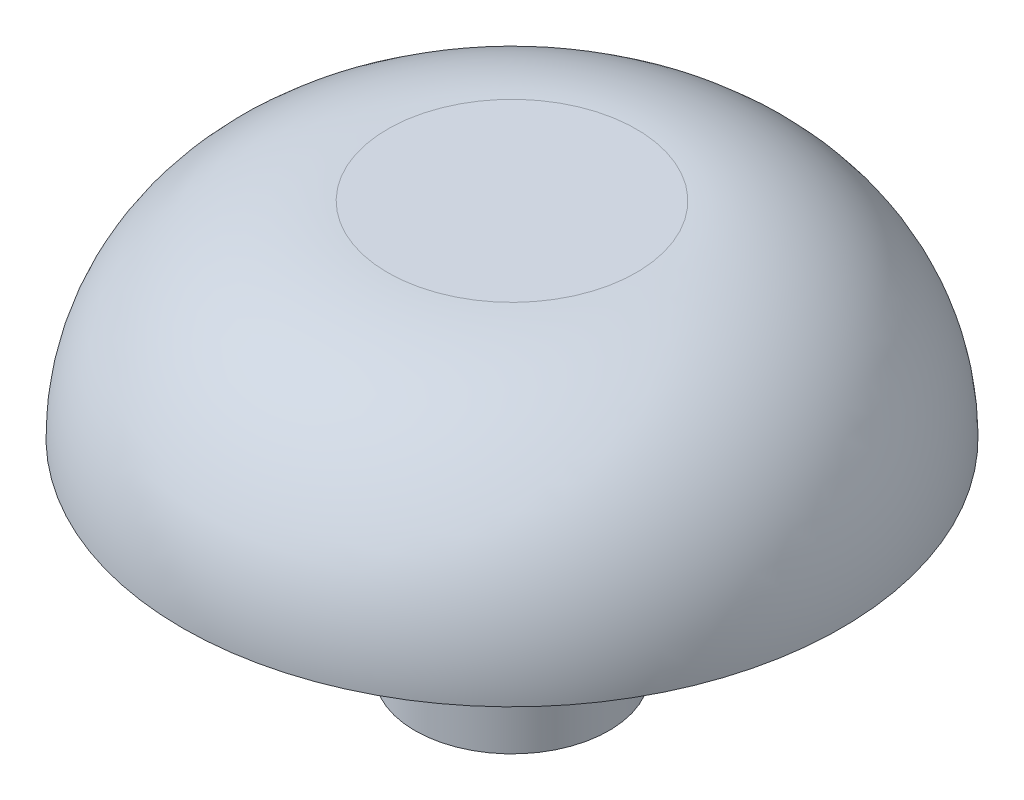
SolidWorks part; units mm, degrees
material "PE Alta Densidade"
ref_plane "Plano frontal" through (0, 0, 0) normal (0, 0, 1) x (1, 0, 0)
ref_plane "Plano superior" through (0, 0, 0) normal (0, 1, 0) x (1, 0, 0)
ref_plane "Plano direito" through (0, 0, 0) normal (1, 0, 0) x (0, 0, -1)
sketch "Esboço1" plane through (0, 0, 0) normal (0, 0, 1) x (1, 0, 0)
  line L0 (0, 0) -> (0, -16.5)
  line L1 (0, 0) -> (5, 0)
  line L2 (2, -2) -> (5, -2) construction
  line L5 (11.25, -8.25) -> (13.25, -8.25)
  line L6 (3.9, -2) -> (5, -2)
  line L8 (0, -16.5) -> (3.9, -16.5)
  line L9 (3.9, -16.5) -> (3.9, -2)
  line L11 (2.0938, -14.5) -> (2.0938, -2) construction
  line L12 (2, -2) -> (2, -14.5) construction
  line L13 (2, -14.5) -> (2.0938, -14.5) construction
  line L14 (0, -16.5) -> (4.0938, -16.5) construction
  line L15 (4.0938, -16.5) -> (4.0938, -2) construction
  arc A0 (5, 0) -> (13.25, -8.25) centre (5, -8.25) cw
  arc A1 (5, -2) -> (11.25, -8.25) centre (5, -8.25) cw
  dimension "D1" = 16.5
  dimension "D5" = 2
  dimension "D2" = 13.25
  dimension "D3" = 5
  dimension "D4" = 3.9
revolve "Revolução1" add sketch "Esboço1" angle 360 about L0
hole_wizard "Furo roscado de M41" positions "Esboço2" profile "Esboço3" tap size "M4" standard "DIN"
sketch "Esboço2" plane through (0, -16.5, 0) normal (0, -1, 0) x (-1, 0, 0)
  point P0 (0, 0)
sketch "Esboço3" plane through (0, -16.5, 0) normal (1, 0, 0) x (0, 0, -1)
  line L0 (0, 0) -> (0, 12.4914)
  line L1 (0, 12.4914) -> (1.65, 11.5)
  line L2 (1.65, 11.5) -> (1.65, 0.375)
  line L3 (1.65, 0.375) -> (2.025, 0)
  line L5 (2.025, 0) -> (0, 0)
  line L6 (-1.65, 0.375) -> (-2.025, 0) construction
  line L10 (0, 12.4914) -> (-1.65, 11.5) construction
  line L11 (0, -6.35) -> (0, 107.95) construction
  dimension "Tap Drill Dia." = 3.3
  dimension "Tap Drill Depth" = 11.5
  dimension "Near C'Sink Dia." = 4.05
  dimension "Near C'Sink Angle" = 90
  dimension "Drill Angle" = 118
cosmetic thread "Rosca de furo1" parameters "D1"=8, "D2"=4
